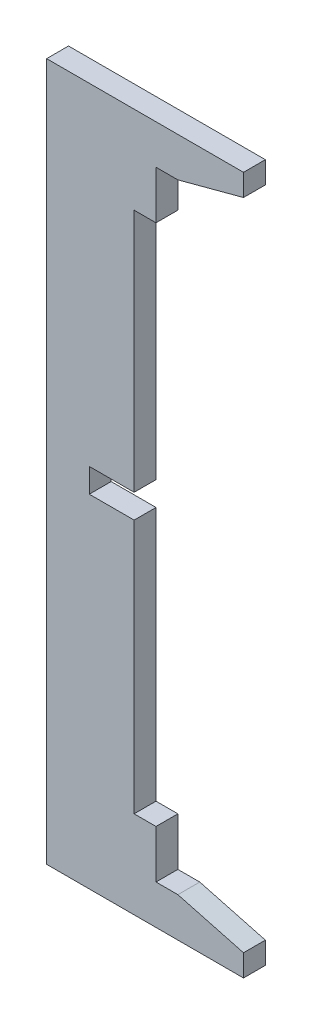
SolidWorks part; units mm, degrees
material "Plain Carbon Steel"
ref_plane "Front Plane" through (0, 0, 0) normal (0, 0, 1) x (1, 0, 0)
ref_plane "Top Plane" through (0, 0, 0) normal (0, 1, 0) x (1, 0, 0)
ref_plane "Right Plane" through (0, 0, 0) normal (1, 0, 0) x (0, 0, -1)
sketch "Model" plane through (0, 0, 0) normal (0, 0, 1) x (1, 0, 0)
  line L0 (-386.253, -153.7291) -> (-386.253, 5.7709)
  line L1 (-356.253, -144.7291) -> (-341.253, -148.7291)
  line L2 (-366.253, -14.2291) -> (-361.253, -14.2291)
  line L3 (-361.253, -14.2291) -> (-361.253, -3.2291)
  line L4 (-361.253, -3.2291) -> (-356.253, -3.2291)
  line L5 (-356.253, -3.2291) -> (-341.253, 0.7709)
  line L6 (-341.253, 0.7709) -> (-341.253, 5.7709)
  line L7 (-341.253, 5.7709) -> (-386.253, 5.7709)
  line L8 (-341.253, -153.7291) -> (-386.253, -153.7291)
  line L9 (-341.253, -148.7291) -> (-341.253, -153.7291)
  line L10 (-361.253, -144.7291) -> (-356.253, -144.7291)
  line L11 (-361.253, -133.7291) -> (-361.253, -144.7291)
  line L12 (-366.253, -133.7291) -> (-361.253, -133.7291)
  line L13 (-366.253, -133.7291) -> (-366.253, -75.5795)
  line L14 (-376.503, -75.5795) -> (-366.253, -75.5795)
  line L15 (-376.503, -70.0795) -> (-376.503, -75.5795)
  line L16 (-366.253, -70.0795) -> (-376.503, -70.0795)
  line L17 (-366.253, -70.0795) -> (-366.253, -14.2291)
  line L18 (-381.253, -33.4041) -> (-381.253, -49.7133)
  line L19 (-371.6371, -41.6336) -> (-371.7089, -42.5015)
  line L20 (-372.2303, -39.5451) -> (-371.9243, -40.0227)
  line L21 (-371.9243, -43.2321) -> (-372.2365, -43.7191)
  line L22 (-371.7089, -40.7564) -> (-371.9243, -40.0227)
  line L23 (-372.4066, -39.4256) -> (-372.5986, -39.3858)
  line L24 (-372.5986, -39.3858) -> (-379.2915, -39.3858)
  line L25 (-379.2915, -39.3858) -> (-379.4889, -39.4256)
  line L26 (-372.4113, -37.8592) -> (-372.5986, -37.8997)
  line L27 (-372.4113, -37.8592) -> (-372.2365, -37.7374)
  line L28 (-372.2303, -39.5451) -> (-372.4066, -39.4256)
  line L29 (-371.9243, -37.2504) -> (-371.7089, -36.5198)
  line L30 (-372.2365, -43.7191) -> (-372.4113, -43.8409)
  line L31 (-372.4113, -43.8409) -> (-372.5986, -43.8815)
  line L32 (-372.5986, -43.8815) -> (-373.2105, -43.8815)
  line L33 (-371.9243, -43.2321) -> (-371.7089, -42.5015)
  line L34 (-372.5986, -37.8997) -> (-373.2105, -37.8997)
  line L35 (-372.2365, -37.7374) -> (-371.9243, -37.2504)
  line L36 (-371.7089, -40.7564) -> (-371.6371, -41.6336)
  line L37 (-379.4889, -39.4256) -> (-379.6692, -39.5451)
  line L38 (-379.6692, -39.5451) -> (-379.9783, -40.0227)
  line L39 (-379.9783, -40.0227) -> (-380.1843, -40.7439)
  line L40 (-380.1843, -40.7439) -> (-380.253, -41.6336)
  line L41 (-380.253, -41.6336) -> (-380.1843, -42.5203)
  line L42 (-380.1843, -42.5203) -> (-379.9783, -43.2321)
  line L43 (-379.9783, -43.2321) -> (-379.663, -43.7191)
  line L44 (-379.4889, -33.4439) -> (-379.2915, -33.4041)
  line L45 (-379.2915, -33.4041) -> (-372.5986, -33.4041)
  line L46 (-372.5986, -33.4041) -> (-372.4066, -33.4439)
  line L47 (-372.2303, -33.5634) -> (-371.9243, -34.041)
  line L48 (-371.9243, -34.041) -> (-371.7089, -34.7747)
  line L49 (-371.7089, -34.7747) -> (-371.6371, -35.6519)
  line L50 (-379.4842, -37.8592) -> (-379.663, -37.7374)
  line L51 (-380.1843, -36.5386) -> (-380.253, -35.6519)
  line L52 (-372.4066, -33.4439) -> (-372.2303, -33.5634)
  line L53 (-371.6371, -35.6519) -> (-371.7089, -36.5198)
  line L54 (-378.6796, -37.8997) -> (-379.2915, -37.8997)
  line L55 (-379.2915, -37.8997) -> (-379.4842, -37.8592)
  line L56 (-380.253, -35.6519) -> (-380.1843, -34.7622)
  line L57 (-380.1843, -34.7622) -> (-379.9783, -34.041)
  line L58 (-379.9783, -34.041) -> (-379.6692, -33.5634)
  line L59 (-379.663, -37.7374) -> (-379.9783, -37.2504)
  line L60 (-379.9783, -37.2504) -> (-380.1843, -36.5386)
  line L61 (-379.6692, -33.5634) -> (-379.4889, -33.4439)
  line L62 (-379.972, -49.2201) -> (-380.1827, -48.4973)
  line L63 (-379.663, -43.7191) -> (-379.4842, -43.8409)
  line L64 (-379.2915, -43.8815) -> (-378.6796, -43.8815)
  line L65 (-374.9788, -48.4973) -> (-374.9086, -47.6154)
  line L66 (-379.4838, -45.4077) -> (-379.2915, -45.3675)
  line L67 (-375.1084, -46.2667) -> (-375.3613, -45.8046)
  line L68 (-380.1827, -46.7334) -> (-379.972, -46.0106)
  line L69 (-379.6614, -49.7024) -> (-379.972, -49.2201)
  line L70 (-374.9086, -47.6154) -> (-375.1084, -46.2667)
  line L71 (-371.6371, -45.3675) -> (-375.8702, -45.3675)
  line L72 (-380.1827, -48.4973) -> (-380.253, -47.6154)
  line L73 (-371.6371, -49.7133) -> (-371.6371, -45.3675)
  line L74 (-379.972, -46.0106) -> (-379.6614, -45.5283)
  line L75 (-379.4838, -49.823) -> (-379.6614, -49.7024)
  line L76 (-379.4838, -49.823) -> (-379.2915, -49.8632)
  line L77 (-375.5002, -49.7024) -> (-375.6777, -49.823)
  line L78 (-375.5002, -49.7024) -> (-375.1895, -49.2201)
  line L79 (-375.8702, -45.3675) -> (-375.3613, -45.8046)
  line L80 (-374.9788, -48.4973) -> (-375.1895, -49.2201)
  line L81 (-375.8702, -49.8632) -> (-379.2915, -49.8632)
  line L82 (-375.6777, -49.823) -> (-375.8702, -49.8632)
  line L83 (-380.253, -47.6154) -> (-380.1827, -46.7334)
  line L84 (-379.4842, -43.8409) -> (-379.2915, -43.8815)
  line L85 (-379.4838, -45.4077) -> (-379.6614, -45.5283)
  line L86 (-383.503, -72.8295) -> (-378.503, -72.8295)
  line L87 (-380.503, -73.8295) -> (-378.503, -72.8295)
  line L88 (-380.503, -71.8295) -> (-378.503, -72.8295)
  line L89 (-383.3656, -76.6479) -> (-383.4686, -77.0085)
  line L90 (-383.3656, -78.2526) -> (-383.208, -78.4961)
  line L91 (-383.208, -78.4961) -> (-383.1186, -78.557)
  line L92 (-383.3656, -76.6479) -> (-383.2111, -76.4091)
  line L93 (-383.1209, -76.3494) -> (-383.0222, -76.3295)
  line L94 (-379.9817, -78.5773) -> (-379.6758, -78.5773)
  line L95 (-379.3386, -78.2526) -> (-379.2309, -77.8873)
  line L96 (-383.4686, -77.0085) -> (-383.503, -77.4534)
  line L97 (-379.5798, -76.3494) -> (-379.4916, -76.4091)
  line L98 (-383.3656, -78.2526) -> (-383.4686, -77.8967)
  line L99 (-379.4916, -76.4091) -> (-379.3386, -76.6479)
  line L100 (-379.195, -77.4534) -> (-379.2309, -77.0147)
  line L101 (-383.2111, -76.4091) -> (-383.1209, -76.3494)
  line L102 (-383.0222, -78.5773) -> (-383.1186, -78.557)
  line L103 (-383.0222, -76.3295) -> (-379.6758, -76.3295)
  line L104 (-379.6758, -76.3295) -> (-379.5798, -76.3494)
  line L105 (-382.7163, -78.5773) -> (-383.0222, -78.5773)
  line L106 (-379.4947, -78.4961) -> (-379.5821, -78.557)
  line L107 (-383.4686, -77.8967) -> (-383.503, -77.4534)
  line L108 (-379.6758, -78.5773) -> (-379.5821, -78.557)
  line L109 (-379.4947, -78.4961) -> (-379.3386, -78.2526)
  line L110 (-379.2309, -77.8873) -> (-379.195, -77.4534)
  line L111 (-379.2309, -77.0147) -> (-379.3386, -76.6479)
  line L112 (-379.195, -80.3381) -> (-379.2309, -80.7674)
  line L113 (-383.1209, -81.4413) -> (-383.0222, -81.462)
  line L114 (-379.6759, -81.462) -> (-379.5822, -81.4413)
  line L115 (-379.195, -79.3203) -> (-381.3051, -79.3203)
  line L116 (-381.7672, -81.462) -> (-381.6142, -81.4042)
  line L117 (-383.503, -83.4412) -> (-383.4679, -83.0002)
  line L118 (-383.0222, -82.3173) -> (-383.1184, -82.3374)
  line L119 (-381.3738, -80.8954) -> (-381.3051, -80.3381)
  line L120 (-379.2309, -80.7674) -> (-379.3386, -81.1311)
  line L121 (-379.195, -84.4902) -> (-379.195, -82.3173)
  line L122 (-383.3656, -81.1311) -> (-383.4686, -80.7705)
  line L123 (-381.48, -81.231) -> (-381.3738, -80.8954)
  line L124 (-379.4947, -81.3793) -> (-379.5822, -81.4413)
  line L125 (-380.9978, -81.4042) -> (-381.1367, -81.231)
  line L126 (-383.4679, -83.0002) -> (-383.3625, -82.6388)
  line L127 (-379.195, -79.3203) -> (-379.195, -80.3381)
  line L128 (-383.503, -80.3381) -> (-383.4686, -80.7705)
  line L129 (-383.0222, -81.462) -> (-381.7672, -81.462)
  line L130 (-381.6142, -81.4042) -> (-381.48, -81.231)
  line L131 (-383.2072, -82.3977) -> (-383.1184, -82.3374)
  line L132 (-380.8434, -81.462) -> (-379.6759, -81.462)
  line L133 (-381.3051, -80.3381) -> (-381.3051, -79.3203)
  line L134 (-383.503, -79.3203) -> (-383.503, -80.3381)
  line L135 (-381.2413, -80.8891) -> (-381.3051, -80.3381)
  line L136 (-381.2413, -80.8891) -> (-381.1367, -81.231)
  line L137 (-379.4947, -81.3793) -> (-379.3386, -81.1311)
  line L138 (-380.8434, -81.462) -> (-380.9978, -81.4042)
  line L139 (-383.3625, -82.6388) -> (-383.2072, -82.3977)
  line L140 (-383.3656, -81.1311) -> (-383.2111, -81.3793)
  line L141 (-383.1209, -81.4413) -> (-383.2111, -81.3793)
  line L142 (-381.3116, -84.5651) -> (-383.0222, -84.5651)
  line L143 (-383.2072, -84.4847) -> (-383.3625, -84.2435)
  line L144 (-380.8308, -83.4412) -> (-380.8659, -83.8822)
  line L145 (-381.3116, -82.3173) -> (-381.0571, -82.5358)
  line L146 (-383.3625, -84.2435) -> (-383.4679, -83.8822)
  line L147 (-380.9307, -82.7668) -> (-380.8308, -83.4412)
  line L148 (-380.9712, -84.2435) -> (-381.1266, -84.4847)
  line L149 (-383.4679, -83.8822) -> (-383.503, -83.4412)
  line L150 (-381.1266, -84.4847) -> (-381.2154, -84.545)
  line L151 (-379.195, -82.3173) -> (-381.3116, -82.3173)
  line L152 (-381.3051, -79.3203) -> (-383.503, -79.3203)
  line L153 (-381.2154, -84.545) -> (-381.3116, -84.5651)
  line L154 (-383.0222, -84.5651) -> (-383.1184, -84.545)
  line L155 (-380.8659, -83.8822) -> (-380.9712, -84.2435)
  line L156 (-383.1184, -84.545) -> (-383.2072, -84.4847)
  line L157 (-381.0571, -82.5358) -> (-380.9307, -82.7668)
  line L158 (-368.253, -8.7291) -> (-363.253, -8.7291)
  line L159 (-365.253, -9.7291) -> (-363.253, -8.7291)
  line L160 (-365.253, -7.7291) -> (-363.253, -8.7291)
  line L161 (-373.0801, -6.8591) -> (-372.7742, -6.8591)
  line L162 (-373.1765, -6.8388) -> (-373.0801, -6.8591)
  line L163 (-373.5609, -11.723) -> (-373.5258, -11.282)
  line L164 (-369.6377, -4.6312) -> (-369.7337, -4.6113)
  line L165 (-373.1763, -10.6192) -> (-373.2651, -10.6795)
  line L166 (-369.2469, -8.6636) -> (-371.7382, -8.0517)
  line L167 (-373.2659, -6.7779) -> (-373.1765, -6.8388)
  line L168 (-373.4236, -6.5344) -> (-373.2659, -6.7779)
  line L169 (-369.2889, -5.2966) -> (-369.3966, -4.9298)
  line L170 (-369.253, -10.5991) -> (-371.3695, -10.5991)
  line L171 (-371.3695, -10.5991) -> (-371.115, -10.8176)
  line L172 (-373.1763, -10.6192) -> (-373.0801, -10.5991)
  line L173 (-371.7382, -8.0517) -> (-371.7439, -9.313)
  line L174 (-373.5266, -5.2903) -> (-373.5609, -5.7352)
  line L175 (-369.253, -10.5991) -> (-369.253, -12.772)
  line L176 (-371.115, -10.8176) -> (-370.9886, -11.0487)
  line L177 (-370.9886, -11.0487) -> (-370.8887, -11.723)
  line L178 (-369.7337, -6.8591) -> (-369.6401, -6.8388)
  line L179 (-369.7337, -4.6113) -> (-373.0801, -4.6113)
  line L180 (-373.269, -4.6909) -> (-373.4236, -4.9298)
  line L181 (-373.5609, -5.7352) -> (-373.5266, -6.1785)
  line L182 (-373.5609, -9.7875) -> (-371.7439, -9.313)
  line L183 (-371.7439, -9.313) -> (-369.2469, -8.6636)
  line L184 (-373.5258, -11.282) -> (-373.4204, -10.9207)
  line L185 (-373.4236, -4.9298) -> (-373.5266, -5.2903)
  line L186 (-369.5495, -4.6909) -> (-369.6377, -4.6312)
  line L187 (-369.3966, -6.5344) -> (-369.2889, -6.1692)
  line L188 (-369.2889, -6.1692) -> (-369.253, -5.7352)
  line L189 (-369.3966, -4.9298) -> (-369.5495, -4.6909)
  line L190 (-373.1789, -4.6312) -> (-373.269, -4.6909)
  line L191 (-373.2651, -10.6795) -> (-373.4204, -10.9207)
  line L192 (-369.7337, -6.8591) -> (-370.0397, -6.8591)
  line L193 (-369.253, -5.7352) -> (-369.2889, -5.2966)
  line L194 (-373.0801, -4.6113) -> (-373.1789, -4.6312)
  line L195 (-369.6401, -6.8388) -> (-369.5527, -6.7779)
  line L196 (-373.5266, -6.1785) -> (-373.4236, -6.5344)
  line L197 (-369.5527, -6.7779) -> (-369.3966, -6.5344)
  line L198 (-373.1763, -12.8268) -> (-373.2651, -12.7665)
  line L199 (-373.2651, -12.7665) -> (-373.4204, -12.5254)
  line L200 (-371.0292, -12.5254) -> (-371.1845, -12.7665)
  line L201 (-373.4204, -12.5254) -> (-373.5258, -12.164)
  line L202 (-370.9238, -12.164) -> (-371.0292, -12.5254)
  line L203 (-370.8887, -11.723) -> (-370.9238, -12.164)
  line L204 (-371.7382, -8.0517) -> (-373.5609, -7.6022)
  line L205 (-371.1845, -12.7665) -> (-371.2733, -12.8268)
  line L206 (-373.0801, -12.8469) -> (-373.1763, -12.8268)
  line L207 (-373.5258, -12.164) -> (-373.5609, -11.723)
  line L208 (-371.2733, -12.8268) -> (-371.3695, -12.8469)
  line L209 (-371.3695, -12.8469) -> (-373.0801, -12.8469)
  line L210 (-368.253, -139.2291) -> (-363.253, -139.2291)
  line L211 (-365.253, -140.2291) -> (-363.253, -139.2291)
  line L212 (-365.253, -138.2291) -> (-363.253, -139.2291)
  line L213 (-373.0801, -137.3591) -> (-372.7742, -137.3591)
  line L214 (-373.1765, -137.3388) -> (-373.0801, -137.3591)
  line L215 (-373.5609, -142.223) -> (-373.5258, -141.782)
  line L216 (-369.6377, -135.1312) -> (-369.7337, -135.1113)
  line L217 (-373.1763, -141.1192) -> (-373.2651, -141.1795)
  line L218 (-369.2469, -139.1636) -> (-371.7382, -138.5517)
  line L219 (-373.2659, -137.2779) -> (-373.1765, -137.3388)
  line L220 (-373.4236, -137.0344) -> (-373.2659, -137.2779)
  line L221 (-369.2889, -135.7965) -> (-369.3966, -135.4297)
  line L222 (-369.253, -141.0991) -> (-371.3695, -141.0991)
  line L223 (-371.3695, -141.0991) -> (-371.115, -141.3176)
  line L224 (-373.1763, -141.1192) -> (-373.0801, -141.0991)
  line L225 (-371.7382, -138.5517) -> (-371.7439, -139.813)
  line L226 (-373.5266, -135.7903) -> (-373.5609, -136.2352)
  line L227 (-369.253, -141.0991) -> (-369.253, -143.272)
  line L228 (-371.115, -141.3176) -> (-370.9886, -141.5486)
  line L229 (-370.9886, -141.5486) -> (-370.8887, -142.223)
  line L230 (-369.7337, -137.3591) -> (-369.6401, -137.3388)
  line L231 (-369.7337, -135.1113) -> (-373.0801, -135.1113)
  line L232 (-373.269, -135.1909) -> (-373.4236, -135.4297)
  line L233 (-373.5609, -136.2352) -> (-373.5266, -136.6785)
  line L234 (-373.5609, -140.2875) -> (-371.7439, -139.813)
  line L235 (-371.7439, -139.813) -> (-369.2469, -139.1636)
  line L236 (-373.5258, -141.782) -> (-373.4204, -141.4206)
  line L237 (-373.4236, -135.4297) -> (-373.5266, -135.7903)
  line L238 (-369.5495, -135.1909) -> (-369.6377, -135.1312)
  line L239 (-369.3966, -137.0344) -> (-369.2889, -136.6691)
  line L240 (-369.2889, -136.6691) -> (-369.253, -136.2352)
  line L241 (-369.3966, -135.4297) -> (-369.5495, -135.1909)
  line L242 (-373.1789, -135.1312) -> (-373.269, -135.1909)
  line L243 (-373.2651, -141.1795) -> (-373.4204, -141.4206)
  line L244 (-369.7337, -137.3591) -> (-370.0397, -137.3591)
  line L245 (-369.253, -136.2352) -> (-369.2889, -135.7965)
  line L246 (-373.0801, -135.1113) -> (-373.1789, -135.1312)
  line L247 (-369.6401, -137.3388) -> (-369.5527, -137.2779)
  line L248 (-373.5266, -136.6785) -> (-373.4236, -137.0344)
  line L249 (-369.5527, -137.2779) -> (-369.3966, -137.0344)
  line L250 (-373.1763, -143.3268) -> (-373.2651, -143.2665)
  line L251 (-373.2651, -143.2665) -> (-373.4204, -143.0253)
  line L252 (-371.0292, -143.0253) -> (-371.1845, -143.2665)
  line L253 (-373.4204, -143.0253) -> (-373.5258, -142.664)
  line L254 (-370.9238, -142.664) -> (-371.0292, -143.0253)
  line L255 (-370.8887, -142.223) -> (-370.9238, -142.664)
  line L256 (-371.7382, -138.5517) -> (-373.5609, -138.1021)
  line L257 (-371.1845, -143.2665) -> (-371.2733, -143.3268)
  line L258 (-373.0801, -143.3469) -> (-373.1763, -143.3268)
  line L259 (-373.5258, -142.664) -> (-373.5609, -142.223)
  line L260 (-371.2733, -143.3268) -> (-371.3695, -143.3469)
  line L261 (-371.3695, -143.3469) -> (-373.0801, -143.3469)
sketch "Sketch2" plane through (0, 0, 0) normal (0, 0, 1) x (1, 0, 0)
  line L0 (-366.253, -70.0795) -> (-376.503, -70.0795) construction
  line L1 (-376.503, -70.0795) -> (-376.503, -75.5795) construction
  line L2 (-376.503, -75.5795) -> (-366.253, -75.5795) construction
  line L3 (-366.253, -133.7291) -> (-366.253, -75.5795) construction
  line L4 (-366.253, -133.7291) -> (-361.253, -133.7291) construction
  line L5 (-361.253, -133.7291) -> (-361.253, -144.7291) construction
  line L6 (-361.253, -144.7291) -> (-356.253, -144.7291) construction
  line L7 (-356.253, -144.7291) -> (-341.253, -148.7291) construction
  line L8 (-341.253, -148.7291) -> (-341.253, -153.7291) construction
  line L9 (-341.253, -153.7291) -> (-386.253, -153.7291) construction
  line L10 (-386.253, -153.7291) -> (-386.253, 5.7709) construction
  line L11 (-341.253, 5.7709) -> (-386.253, 5.7709) construction
  line L12 (-341.253, 0.7709) -> (-341.253, 5.7709) construction
  line L13 (-356.253, -3.2291) -> (-341.253, 0.7709) construction
  line L14 (-361.253, -3.2291) -> (-356.253, -3.2291) construction
  line L15 (-361.253, -14.2291) -> (-361.253, -3.2291) construction
  line L16 (-366.253, -14.2291) -> (-361.253, -14.2291) construction
  line L17 (-366.253, -70.0795) -> (-366.253, -14.2291) construction
  line L18 (-366.253, -70.0795) -> (-376.503, -70.0795)
  line L19 (-376.503, -70.0795) -> (-376.503, -75.5795)
  line L20 (-376.503, -75.5795) -> (-366.253, -75.5795)
  line L21 (-366.253, -133.7291) -> (-366.253, -75.5795)
  line L22 (-366.253, -133.7291) -> (-361.253, -133.7291)
  line L23 (-361.253, -133.7291) -> (-361.253, -144.7291)
  line L24 (-361.253, -144.7291) -> (-356.253, -144.7291)
  line L25 (-356.253, -144.7291) -> (-341.253, -148.7291)
  line L26 (-341.253, -148.7291) -> (-341.253, -153.7291)
  line L27 (-341.253, -153.7291) -> (-386.253, -153.7291)
  line L28 (-386.253, -153.7291) -> (-386.253, 5.7709)
  line L29 (-341.253, 5.7709) -> (-386.253, 5.7709)
  line L30 (-341.253, 0.7709) -> (-341.253, 5.7709)
  line L31 (-356.253, -3.2291) -> (-341.253, 0.7709)
  line L32 (-361.253, -3.2291) -> (-356.253, -3.2291)
  line L33 (-361.253, -14.2291) -> (-361.253, -3.2291)
  line L34 (-366.253, -14.2291) -> (-361.253, -14.2291)
  line L35 (-366.253, -70.0795) -> (-366.253, -14.2291)
extrude "Boss-Extrude1" add sketch "Sketch2" along normal mid plane 5
ref_plane "Plane1" through (0, -72.8295, 0) normal (0, 1, 0) x (1, 0, 0)
